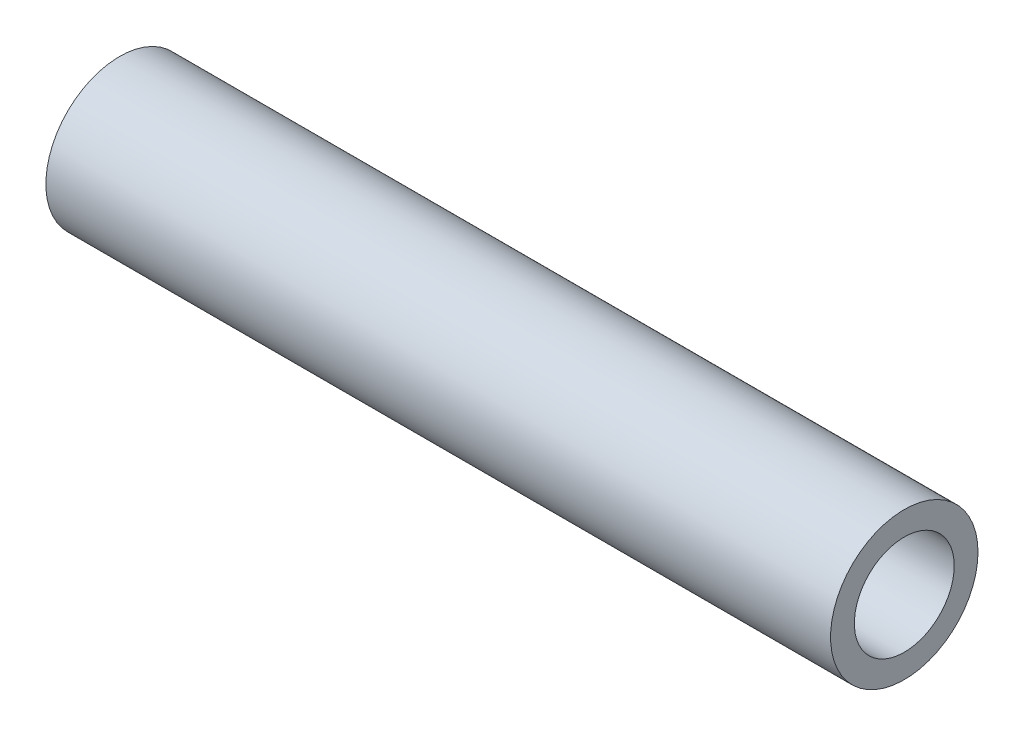
SolidWorks part; units mm, degrees
ref_plane "Ön Düzlem" through (0, 0, 0) normal (1, 0, 0) x (0, 1, 0)
ref_plane "Üst Düzlem" through (0, 0, 0) normal (0, 0, 1) x (0, 1, 0)
ref_plane "Sağ Düzlem" through (0, 0, 0) normal (0, 1, 0) x (-1, 0, 0)
sketch "Çizim1" plane through (0, 0, 0) normal (1, 0, 0) x (0, 1, 0)
  circle A0 centre (0, 0) radius 2.1
  circle A1 centre (0, 0) radius 3.1
  dimension "D1" = 4.2
  dimension "D2" = 6.2
extrude "Yükseklik-Ekstrüzyon1" add sketch "Çizim1" along normal blind 33
